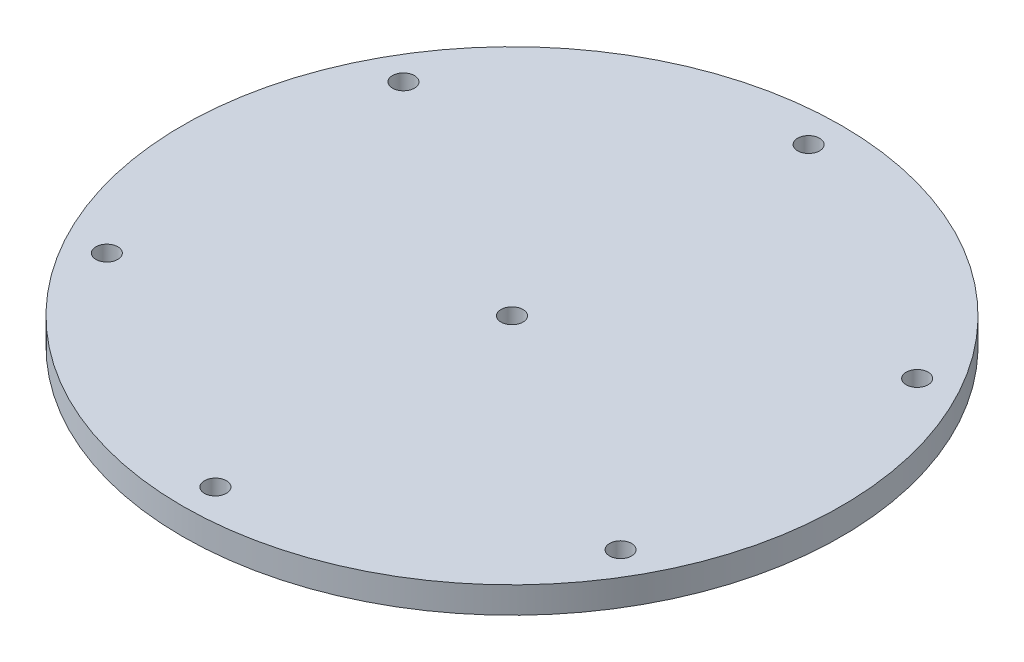
SolidWorks part; units mm, degrees
ref_plane "Front Plane" through (0, 0, 0) normal (0, 0, 1) x (1, 0, 0)
ref_plane "Top Plane" through (0, 0, 0) normal (0, 1, 0) x (1, 0, 0)
ref_plane "Right Plane" through (0, 0, 0) normal (1, 0, 0) x (0, 0, -1)
sketch "Sketch1" plane through (0, 0, 0) normal (0, 1, 0) x (1, 0, 0)
  circle A0 centre (0, 0) radius 75
  circle A1 centre (0, 0) radius 67.5 construction
  circle A2 centre (0, 67.5) radius 2.5
  circle A3 centre (58.4567, 33.75) radius 2.5
  circle A4 centre (58.4567, -33.75) radius 2.5
  circle A5 centre (0, -67.5) radius 2.5
  circle A6 centre (-58.4567, -33.75) radius 2.5
  circle A7 centre (-58.4567, 33.75) radius 2.5
  circle A8 centre (0, 0) radius 2.5
  point P18 (0, 0)
  dimension "D1" = 6
  dimension "D2" = 135
  dimension "D3" = 150
  dimension "D4" = 5
  dimension "D5" = 5
extrude "Boss-Extrude1" add sketch "Sketch1" along normal blind 6
